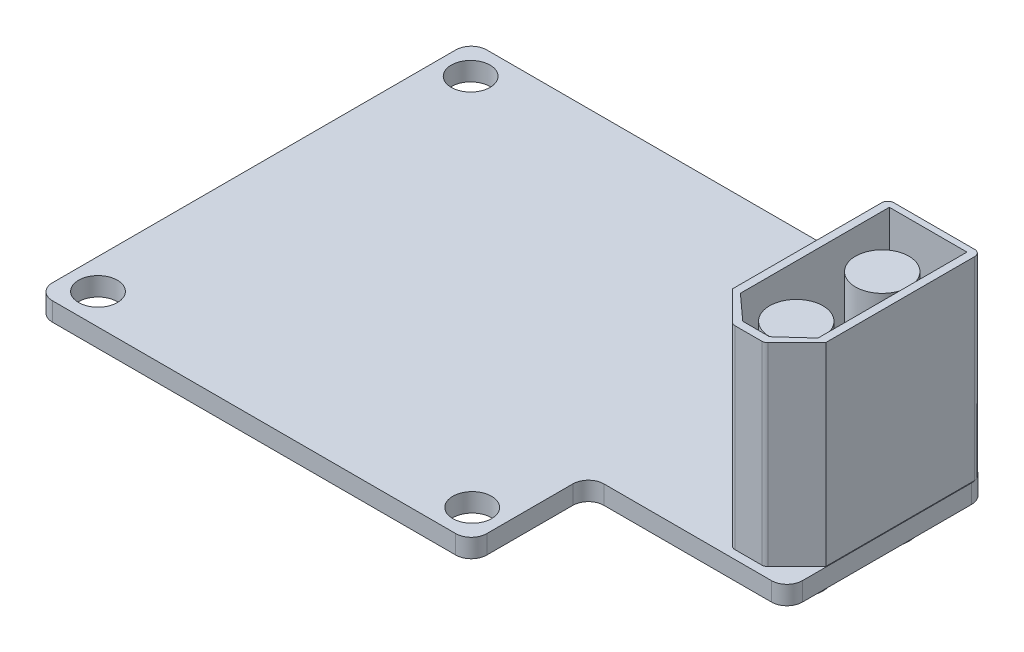
SolidWorks part; units mm, degrees
ref_plane "Front Plane" through (0, 0, 0) normal (0, 0, 1) x (1, 0, 0)
ref_plane "Top Plane" through (0, 0, 0) normal (0, 1, 0) x (1, 0, 0)
ref_plane "Right Plane" through (0, 0, 0) normal (1, 0, 0) x (0, 0, -1)
sketch "Sketch1" plane through (0, 0, 0) normal (0, 1, 0) x (1, 0, 0)
  line L0 (-50.7462, 35.4274) -> (-17.7262, 35.4274)
  line L1 (-52.0162, 34.1574) -> (-52.0162, 1.1374)
  line L2 (-50.7462, -0.1326) -> (-17.7262, -0.1326)
  line L3 (-16.4562, 1.1374) -> (-16.4562, 8.1859)
  line L5 (-15.1862, 25.8389) -> (-1.4702, 25.8389)
  line L6 (-0.2002, 24.5689) -> (-0.2002, 10.7259)
  line L9 (-15.1862, 9.4559) -> (-1.4702, 9.4559)
  line L11 (-16.4562, 27.1089) -> (-16.4562, 34.1574)
  circle A0 centre (-49.5397, 32.9001) radius 1.5875
  circle A1 centre (-18.9073, 32.9001) radius 1.5875
  circle A2 centre (-18.9073, 2.3947) radius 1.5875
  circle A3 centre (-49.5397, 2.3947) radius 1.5875
  arc A4 (-50.7462, 35.4274) -> (-52.0162, 34.1574) centre (-50.7462, 34.1574) ccw
  arc A5 (-52.0162, 1.1374) -> (-50.7462, -0.1326) centre (-50.7462, 1.1374) ccw
  arc A6 (-17.7262, -0.1326) -> (-16.4562, 1.1374) centre (-17.7262, 1.1374) ccw
  arc A7 (-17.7262, 35.4274) -> (-16.4562, 34.1574) centre (-17.7262, 34.1574) cw
  circle A8 centre (-4.1118, 21.1653) radius 2.1844
  circle A10 centre (-4.1118, 14.1295) radius 2.1844
  arc A12 (-1.4702, 25.8389) -> (-0.2002, 24.5689) centre (-1.4702, 24.5689) cw
  arc A13 (-1.4702, 9.4559) -> (-0.2002, 10.7259) centre (-1.4702, 10.7259) ccw
  arc A14 (-15.1862, 9.4559) -> (-16.4562, 8.1859) centre (-15.1862, 8.1859) ccw
  arc A15 (-16.4562, 27.1089) -> (-15.1862, 25.8389) centre (-15.1862, 27.1089) ccw
  point P38 (-16.4562, 25.8389)
  dimension "D1" = 1.27
  dimension "D2" = 1.27
extrude "Boss-Extrude2" add sketch "Sketch1" along normal blind 1.524
sketch "Sketch2" plane through (0, 1.524, 0) normal (0, 1, 0) x (1, 0, 0)
  line L0 (-0.2493, 12.6816) -> (-2.6054, 10.308)
  line L1 (-7.3648, 25.3816) -> (-0.7573, 25.3816)
  line L3 (-0.2493, 24.8736) -> (-0.2493, 12.6816)
  line L4 (-7.8728, 12.6816) -> (-5.5197, 10.3082)
  line L5 (-7.8728, 24.8736) -> (-7.8728, 12.6816)
  line L6 (-5.159, 10.1579) -> (-2.966, 10.1579)
  arc A1 (-5.159, 10.1579) -> (-5.5197, 10.3082) centre (-5.159, 10.6659) cw
  arc A2 (-2.966, 10.1579) -> (-2.6054, 10.308) centre (-2.966, 10.6659) ccw
  arc A3 (-0.7573, 25.3816) -> (-0.2493, 24.8736) centre (-0.7573, 24.8736) cw
  arc A4 (-7.3648, 25.3816) -> (-7.8728, 24.8736) centre (-7.3648, 24.8736) ccw
  dimension "D1" = 0.508
extrude "Boss-Extrude3" add sketch "Sketch2" along normal blind 15.875
sketch "Sketch3" plane through (0, 0, 0) normal (0, -1, 0) x (1, 0, 0)
  circle A0 centre (-4.1118, -14.1295) radius 2.1844
  circle A1 centre (-4.1118, -21.1653) radius 2.1844
extrude "Boss-Extrude4" add sketch "Sketch3" along normal blind 1.778 separate body
sketch "Sketch4" plane through (0, 17.399, 0) normal (0, 1, 0) x (1, 0, 0)
  line L0 (-7.2378, 24.8736) -> (-7.2378, 12.6816)
  line L6 (-5.159, 10.7929) -> (-2.966, 10.7929)
  line L7 (-0.8843, 12.6816) -> (-0.8843, 24.8736)
  line L8 (-0.8843, 24.8736) -> (-7.2378, 24.8736)
  line L10 (-7.2378, 12.6816) -> (-5.159, 10.7929)
  line L11 (-2.966, 10.7929) -> (-0.8843, 12.6816)
extrude "Cut-Extrude1" cut sketch "Sketch4" against normal blind 9.398
sketch "Sketch6" plane through (0, 0, 0) normal (0, -1, 0) x (1, 0, 0)
  circle A0 centre (-4.1118, -14.1295) radius 2.1844
  circle A1 centre (-4.1118, -21.1653) radius 2.1844
extrude "Boss-Extrude5" add sketch "Sketch6" against normal blind 16.256
